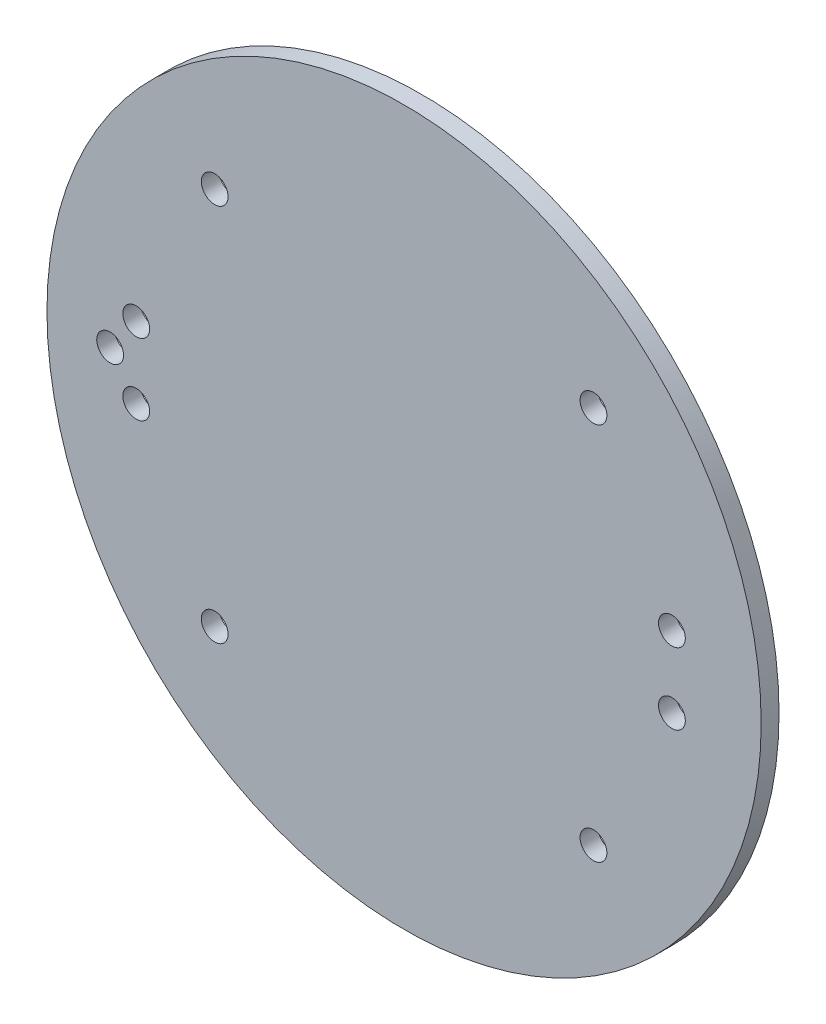
SolidWorks part; units mm, degrees
ref_plane "Front Plane" through (0, 0, 0) normal (0, 0, 1) x (1, 0, 0)
ref_plane "Top Plane" through (0, 0, 0) normal (0, 1, 0) x (1, 0, 0)
ref_plane "Right Plane" through (0, 0, 0) normal (1, 0, 0) x (0, 0, -1)
sketch "Sketch1" plane through (0, 0, 0) normal (0, 0, 1) x (1, 0, 0)
  circle A0 centre (0, 0) radius 127
  dimension "D1" = 254
extrude "Boss-Extrude1" add sketch "Sketch1" along normal blind 6.35
sketch "Sketch2" plane through (0, 0, 6.35) normal (0, 0, 1) x (1, 0, 0)
  line L0 (0, 127) -> (0, -127) construction
  line L1 (-127, 0) -> (127, 0) construction
  line L2 (0, 0) -> (-89.8026, -89.8026) construction
  line L3 (0, 0) -> (89.8026, 89.8026) construction
  line L4 (0, 0) -> (-89.8026, 89.8026) construction
  line L5 (0, 0) -> (89.8026, -89.8026) construction
  circle A0 centre (0, 0) radius 127 construction
  circle A1 centre (-67.3519, 67.3519) radius 4.7625
  circle A2 centre (-67.3519, -67.3519) radius 4.7625
  circle A3 centre (67.3519, -67.3519) radius 4.7625
  circle A4 centre (67.3519, 67.3519) radius 4.7625
  dimension "D1" = 9.525
  dimension "D2" = 95.25
extrude "Cut-Extrude1" cut sketch "Sketch2" against normal through all both and the other way through all
sketch "Sketch3" plane through (0, 0, 6.35) normal (0, 0, 1) x (1, 0, 0)
  line L0 (0, 127) -> (0, -127) construction
  line L1 (-127, 0) -> (127, 0) construction
  line L2 (-126.3634, 12.7) -> (126.3634, 12.7) construction
  circle A0 centre (0, 0) radius 127 construction
  circle A1 centre (-95.25, 12.7) radius 4.7625
  circle A2 centre (-95.25, -12.7) radius 4.7625
  circle A3 centre (95.25, -12.7) radius 4.7625
  circle A4 centre (95.25, 12.7) radius 4.7625
  dimension "D1" = 9.525
  dimension "D2" = 12.7
  dimension "D3" = 95.25
extrude "Cut-Extrude2" cut sketch "Sketch3" against normal through all both and the other way through all
sketch "Sketch4" plane through (0, 0, 6.35) normal (0, 0, 1) x (1, 0, 0)
  line L0 (0, 134.806) -> (0, -133.0899) construction
  line L1 (-151.3672, 0) -> (150.6807, 0) construction
  circle A0 centre (-104.5375, 0) radius 4.7625
  dimension "D1" = 9.525
  dimension "D2" = 104.5375
extrude "Cut-Extrude4" cut sketch "Sketch4" against normal through all both and the other way through all
equation "\"Wheel Thickness\"= 1in"
equation "\"Wheel Diameter\"= 3in"
equation "\"Motor Rear Diameter\" = 36.2mm"
equation "\"Motor Front Diameter\" = 12mm"
equation "\"Material Thickness\" = .25in"
equation "\"Wheel Cutout Diameter\"= 2cm"
equation "\"Motor Mount Tab Thickness\" = 100mm"
equation "\"Motor Mount Tab Height\" = 40mm"
equation "\"Motor Shaft Diameter\" = 3mm"
equation "\"Wheel Radius Clearance\" = 5mm"
equation "\"Wheel Cutout Width\" = 1.5in"
equation "\"Base Diameter\" = 10in"
equation "\"Wheel Mount Distance\" = 5mm"
equation "\"Motor Mount Distance\" = 50mm"
equation "\"Motor Cutout Length\" = 6in"
equation "\"Motor Cutout Height\" = 2in "
equation "\"Rod Diameter\" = 3/8in"
equation "\"Rod Length\" = 1.5in"
equation "\"D1@Sketch1\"=\"Second Level Diameter\""
equation "\"D1@Boss-Extrude1\"=\"Material Thickness\""
equation "\"D1@Sketch2\"=\"Rod Diameter\""
equation "\"D2@Sketch2\"=(\"Base Diameter\"/2)*.75"
equation "\"Barrel Front Length\" = 1.8in"
equation "\"Barrerl Rear Length\" = 5in "
equation "\"Barrel Fillet Radius\" = 1in "
equation "\"Barrel Angle\" = 20deg"
equation "\"Barrel Diameter\" = 50mm"
equation "\"Barrel Shell Width\" = 2mm"
equation "\"Second Level Diameter\" = 10in"
equation "\"Ball Diameter\" = 40mm"
equation "\"D1@Sketch3\"=\"Rod Diameter\""
equation "\"Third Level Length\" = 9in"
equation "\"Third Level Height\" = 9in"
equation "\"Barrel Tab Clearance\" = 5mm"
equation "\"Barrel Tab Distance Away\" = 2mm"
equation "\"Hole Distance Apart\" = 2.8in"
equation "\"Barrel Tab Distance\"= 1.5in "
equation "\"Third Level Rod Distance\" = .5in"
equation "\"D2@Sketch3\"=\"Third Level Rod Distance\""
equation "\"D1@Sketch4\"=\"Rod Diameter\""
equation "\"D2@Sketch4\"=((\"Base Diameter\"/2)-5mm)-((\"Rod Diameter\"/2)+.5)"
